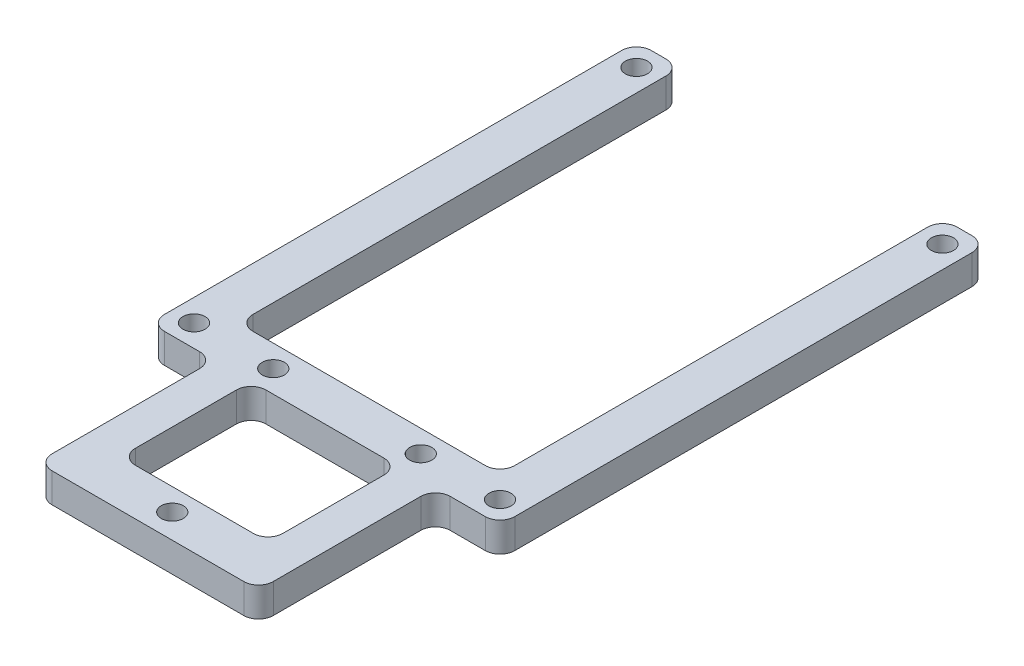
SolidWorks part; units mm, degrees
material "Thornel Mat VMA"
ref_plane "前视基准面" through (0, 0, 0) normal (0, 0, 1) x (1, 0, 0)
ref_plane "上视基准面" through (0, 0, 0) normal (0, 1, 0) x (1, 0, 0)
ref_plane "右视基准面" through (0, 0, 0) normal (1, 0, 0) x (0, 0, -1)
sketch "草图1" plane through (0, 0, 0) normal (0, 1, 0) x (1, 0, 0)
  line L0 (0, 0) -> (0, 90) construction
  line L1 (-23.75, 90) -> (23.75, 90)
  line L2 (-23.75, 90) -> (-23.75, 0)
  line L3 (-23.75, 0) -> (23.75, 0)
  line L4 (23.75, 90) -> (23.75, 0)
  circle A0 centre (-10, 27) radius 1.5
  circle A1 centre (0, 3.3) radius 1.5
  circle A2 centre (10, 27) radius 1.5
  dimension "D3" = 3
  dimension "D4" = 20
  dimension "D5" = 23.7
  dimension "D6" = 3.3
  dimension "D1" = 47.5
  dimension "D2" = 90
extrude "凸台-拉伸1" add sketch "草图1" along normal blind 4
sketch "草图2" plane through (0, 0, 0) normal (0, 1, 0) x (1, 0, 0)
  line L0 (0, 0) -> (0, 90) construction
  line L1 (23.75, 90) -> (-23.75, 90) construction
  line L2 (-23.75, 90) -> (-23.75, 0) construction
  line L3 (-17.75, 90) -> (17.75, 90)
  line L4 (-17.75, 90) -> (-17.75, 30)
  line L5 (-17.75, 30) -> (17.75, 30)
  line L6 (17.75, 90) -> (17.75, 30)
  line L7 (-20.75, 87) -> (-20.75, 27) construction
  line L8 (23.75, 0) -> (23.75, 90) construction
  line L9 (-23.75, 0) -> (23.75, 0) construction
  line L10 (-23.75, 24) -> (-15, 24)
  line L11 (-23.75, 24) -> (-23.75, 0)
  line L12 (-23.75, 0) -> (-15, 0)
  line L13 (-15, 24) -> (-15, 0)
  line L14 (15, 24) -> (15, 0)
  line L15 (23.75, 0) -> (15, 0)
  line L16 (23.75, 24) -> (23.75, 0)
  line L17 (23.75, 24) -> (15, 24)
  line L18 (-10, 27) -> (-10, 24) construction
  line L19 (-10, 24) -> (10, 24)
  line L20 (-10, 24) -> (-10, 6.3)
  line L21 (-10, 6.3) -> (10, 6.3)
  line L22 (10, 24) -> (10, 6.3)
  line L23 (10, 27) -> (10, 24) construction
  circle A0 centre (-10, 27) radius 1.5 construction
  circle A1 centre (-20.75, 87) radius 1.5
  circle A2 centre (20.75, 87) radius 1.5
  circle A3 centre (-20.75, 27) radius 1.5
  circle A4 centre (20.75, 27) radius 1.5
  circle A5 centre (0, 3.3) radius 1.5 construction
  dimension "D5" = 3
  dimension "D6" = 3
  dimension "D7" = 3
  dimension "D1" = 6
  dimension "D2" = 3
  dimension "D4" = 60
  dimension "D8" = 30
  dimension "D9" = 6
  dimension "D10" = 3
  dimension "D11" = 3
  dimension "D3" = 2
extrude "切除-拉伸2" cut sketch "草图2" along normal through all
fillet "圆角1" radius 2 16 edges at (-15, 2, -24) (15, 2, -24) (15, 2, 0) (23.75, 2, -24) (-17.75, 2, -30) (-15, 2, 0) (-23.75, 2, -24) (17.75, 2, -30) (23.75, 2, -90) (17.75, 2, -90) (-17.75, 2, -90) (-23.75, 2, -90) (10, 2, -6.3) (-10, 2, -6.3) (10, 2, -24) (-10, 2, -24)
